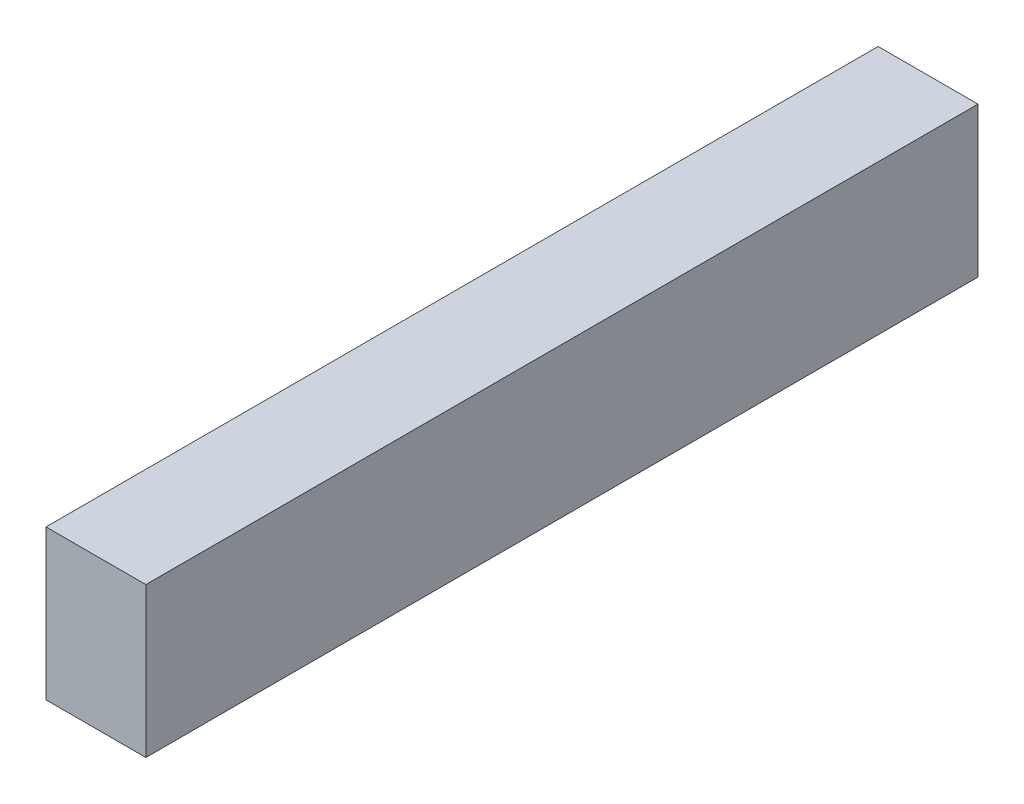
SolidWorks part; units mm, degrees
ref_plane "front" through (0, 0, 0) normal (0, 0, 1) x (1, 0, 0)
ref_plane "top" through (0, 0, 0) normal (0, 1, 0) x (1, 0, 0)
ref_plane "right" through (0, 0, 0) normal (1, 0, 0) x (0, 0, -1)
sketch "Sketch1" plane through (0, 0, 0) normal (0, 0, 1) x (1, 0, 0)
  line L1 (-19.05, 0) -> (19.05, 0)
  line L2 (-19.05, 0) -> (-19.05, -57.15)
  line L3 (-19.05, -57.15) -> (19.05, -57.15)
  line L4 (19.05, 0) -> (19.05, -57.15)
  dimension "D1" = 38.1
  dimension "D2" = 57.15
extrude "Extrude1" add sketch "Sketch1" against normal blind 317.5
